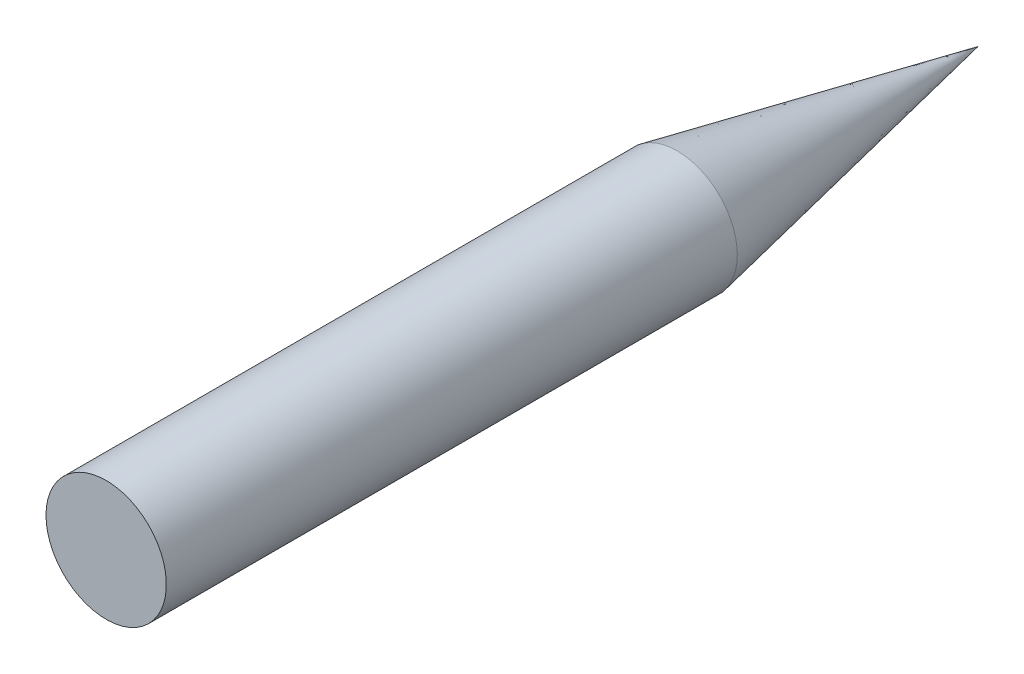
SolidWorks part; units mm, degrees
ref_plane "Front Plane" through (0, 0, 0) normal (0, 0, 1) x (1, 0, 0)
ref_plane "Top Plane" through (0, 0, 0) normal (0, 1, 0) x (1, 0, 0)
ref_plane "Right Plane" through (0, 0, 0) normal (1, 0, 0) x (0, 0, -1)
ref_plane "Plane1" through (0, 0, 0) normal (0, -1, 0) x (1, 0, 0)
sketch "Sketch1" plane through (0, 0, 0) normal (0, -1, 0) x (1, 0, 0)
  line L0 (3.175, 1) -> (0, 1)
  line L1 (0, 1) -> (0, -45)
  line L2 (0, -45) -> (3.175, -29.125)
  line L3 (3.175, -29.125) -> (3.175, 1)
  line L4 (0, 1) -> (0, -45) construction
revolve "Revolve1" add sketch "Sketch1" angle 360 about L4
